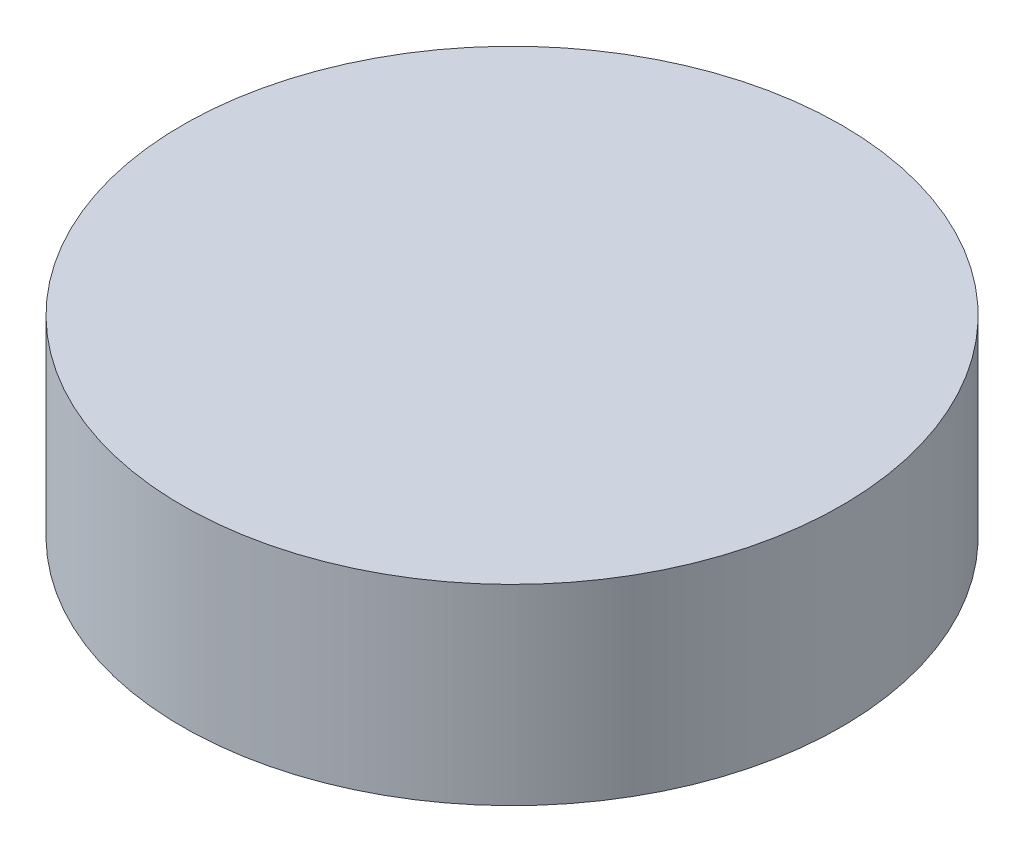
SolidWorks part; units mm, degrees
ref_plane "Front Plane" through (0, 0, 0) normal (0, 0, 1) x (1, 0, 0)
ref_plane "Top Plane" through (0, 0, 0) normal (0, 1, 0) x (1, 0, 0)
ref_plane "Right Plane" through (0, 0, 0) normal (1, 0, 0) x (0, 0, -1)
sketch "Sketch1" plane through (0, 0, 0) normal (0, 0, 1) x (1, 0, 0)
  line L0 (0, 0) -> (43.688, 0)
  line L1 (43.688, 0) -> (43.688, -25.4)
  line L2 (43.688, -25.4) -> (40.513, -25.4)
  line L3 (40.513, -25.4) -> (40.513, -3.175)
  line L4 (40.513, -3.175) -> (0, -3.175)
  line L5 (0, -3.175) -> (0, 0)
  dimension "D1" = 3.175
  dimension "D2" = 3.175
  dimension "D3" = 25.4
  dimension "D4" = 40.513
revolve "Revolve1" add sketch "Sketch1" angle 360 about L5
sketch "Sketch2" plane through (0, -3.175, 0) normal (0, -1, 0) x (1, 0, 0)
  line L1 (-40.513, 0.7937) -> (40.513, 0.7937)
  line L2 (-40.513, 0.7937) -> (-40.513, -0.7937)
  line L3 (-40.513, -0.7937) -> (40.513, -0.7937)
  line L4 (40.513, 0.7937) -> (40.513, -0.7937)
  line L5 (-40.513, 0.7937) -> (40.513, -0.7937) construction
  line L6 (-40.513, -0.7937) -> (40.513, 0.7937) construction
  circle A0 centre (0, 0) radius 40.513 construction
  point P0 (0, 0)
  dimension "D1" = 1.5875
extrude "Boss-Extrude1" add sketch "Sketch2" along normal blind 6.35
